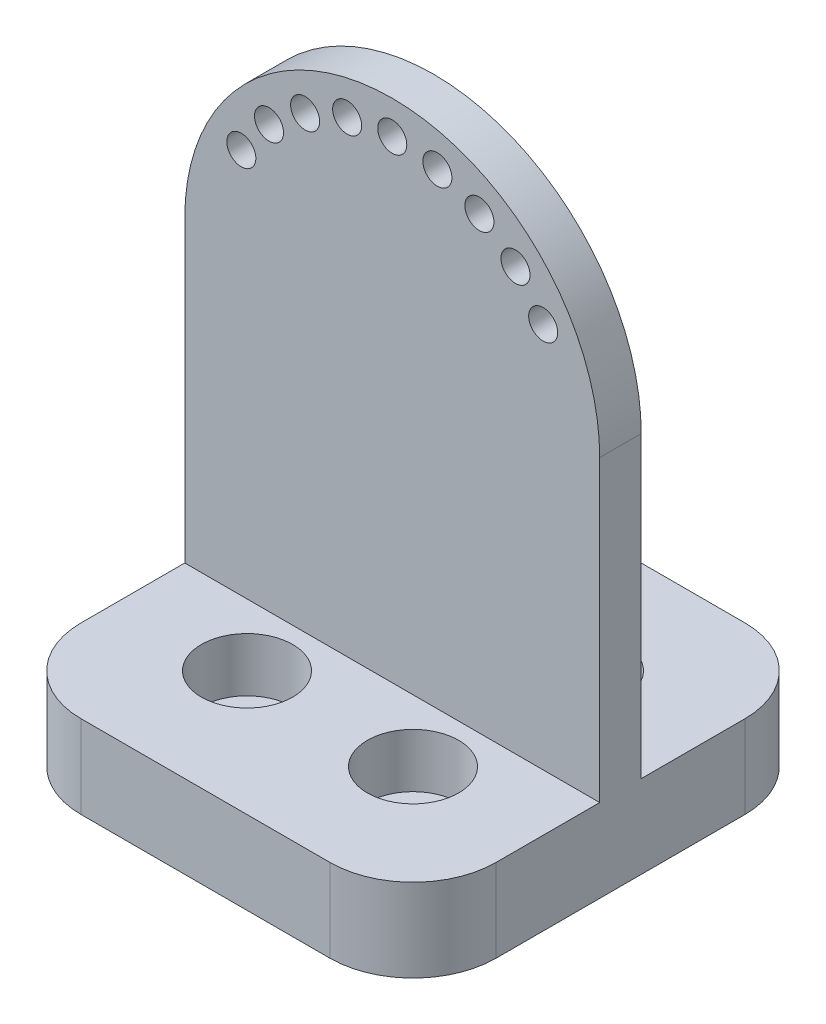
SolidWorks part; units mm, degrees
ref_plane "正面" through (0, 0, 0) normal (0, 0, 1) x (1, 0, 0)
ref_plane "平面" through (0, 0, 0) normal (0, 1, 0) x (1, 0, 0)
ref_plane "右側面" through (0, 0, 0) normal (1, 0, 0) x (0, 0, -1)
sketch "ｽｹｯﾁ1" plane through (0, 0, 0) normal (0, 1, 0) x (1, 0, 0)
  line L1 (25, 25) -> (-25, 25)
  line L2 (25, 25) -> (25, -25)
  line L3 (25, -25) -> (-25, -25)
  line L4 (-25, 25) -> (-25, -25)
  line L5 (25, 25) -> (-25, -25) construction
  line L6 (25, -25) -> (-25, 25) construction
  point P0 (0, 0)
  dimension "D1" = 50
  dimension "D2" = 50
extrude "ﾎﾞｽ - 押し出し1" add sketch "ｽｹｯﾁ1" along normal blind 10
sketch "ｽｹｯﾁ2" plane through (0, 0, 0) normal (0, 0, 1) x (1, 0, 0)
  line L0 (25, 10) -> (-25, 10)
  line L1 (-25, 10) -> (25, 10)
  line L4 (-25, 46) -> (-25, 10)
  line L5 (-25, 10) -> (25, 10)
  line L6 (-12, 10) -> (6.5, 10)
  line L7 (-25, 10) -> (25, 10)
  line L8 (25, 46) -> (25, 10)
  arc A1 (25, 46) -> (-25, 46) centre (0, 46) ccw
  dimension "D1" = 36
  dimension "D3" = 0
  dimension "D2" = 25
  dimension "D4" = 36
  dimension "D5" = 36
extrude "ﾎﾞｽ - 押し出し2" add sketch "ｽｹｯﾁ2" along normal mid plane 5 contours L8 A1 L4 L0 L5
sketch "ｽｹｯﾁ5" plane through (0, 0, 0) normal (0, 0, 1) x (1, 0, 0)
  circle A0 centre (0, 46) radius 21
  circle A1 centre (0, 67) radius 1.75
  circle A2 centre (5.4352, 66.2844) radius 1.75
  circle A3 centre (10.5, 64.1865) radius 1.75
  circle A4 centre (14.8492, 60.8492) radius 1.75
  circle A5 centre (18.1865, 56.5) radius 1.75
  circle A6 centre (20.2844, 51.4352) radius 1.75
  circle A7 centre (21, 46) radius 1.75
  circle A8 centre (20.2844, 40.5648) radius 1.75
  circle A9 centre (18.1865, 35.5) radius 1.75
  circle A10 centre (14.8492, 31.1508) radius 1.75
  circle A11 centre (10.5, 27.8135) radius 1.75
  circle A12 centre (5.4352, 25.7156) radius 1.75
  circle A13 centre (0, 25) radius 1.75
  circle A14 centre (-5.4352, 25.7156) radius 1.75
  circle A15 centre (-10.5, 27.8135) radius 1.75
  circle A16 centre (-14.8492, 31.1508) radius 1.75
  circle A17 centre (-18.1865, 35.5) radius 1.75
  circle A18 centre (-20.2844, 40.5648) radius 1.75
  circle A19 centre (-21, 46) radius 1.75
  circle A20 centre (-20.2844, 51.4352) radius 1.75
  circle A21 centre (-18.1865, 56.5) radius 1.75
  circle A22 centre (-14.8492, 60.8492) radius 1.75
  circle A23 centre (-10.5, 64.1865) radius 1.75
  circle A24 centre (-5.4352, 66.2844) radius 1.75
  point P7 (0.0282, 35.7743)
  point P54 (0, 46)
  dimension "D1" = 42
  dimension "D2" = 3.5
  dimension "D3" = 24
  dimension "D4" = 0
  dimension "D5" = 0
extrude "ｶｯﾄ - 押し出し1" cut sketch "ｽｹｯﾁ5" against normal through all both and the other way through all contours A1 | A24 | A23 | A22 | A21 | A2 | A3 | A4 | A5
sketch "ｽｹｯﾁ6" plane through (0, 0, 0) normal (0, 1, 0) x (1, 0, 0)
  line L0 (0, -25) -> (0, 25) construction
  line L1 (-25, -25) -> (25, -25) construction
  line L2 (25, 25) -> (-25, 25) construction
  line L3 (-25, 0) -> (25, 0) construction
  line L4 (-25, 25) -> (-25, -25) construction
  line L5 (25, -25) -> (25, 25) construction
  circle A0 centre (-10, -10) radius 3.3
  circle A1 centre (10, -10) radius 3.3
  circle A2 centre (10, 10) radius 3.3
  circle A3 centre (-10, 10) radius 3.3
  dimension "D1" = 6.6
  dimension "D2" = 10
  dimension "D3" = 10
extrude "ｶｯﾄ - 押し出し3" cut sketch "ｽｹｯﾁ6" against normal blind 5 and the other way through all
fillet "ﾌｨﾚｯﾄ1" radius 10 4 edges at (-25, 5, 25) (-25, 5, -25) (25, 5, -25) (25, 5, 25)
sketch "ｽｹｯﾁ8" plane through (0, 10, 0) normal (0, 1, 0) x (1, 0, 0)
  line L0 (-25, 0) -> (25, 0) construction
  line L1 (-25, -2.5) -> (-25, 2.5) construction
  line L2 (25, -2.5) -> (25, 2.5) construction
  line L3 (0, 25) -> (0, -25) construction
  line L4 (15, 25) -> (-15, 25) construction
  line L5 (-15, -25) -> (15, -25) construction
  circle A0 centre (-10, -10) radius 5.5
  circle A1 centre (10, -10) radius 5.5
  circle A2 centre (10, 10) radius 5.5
  circle A3 centre (-10, 10) radius 5.5
  dimension "D1" = 11
extrude "ｶｯﾄ - 押し出し5" cut sketch "ｽｹｯﾁ8" against normal blind 6.5
